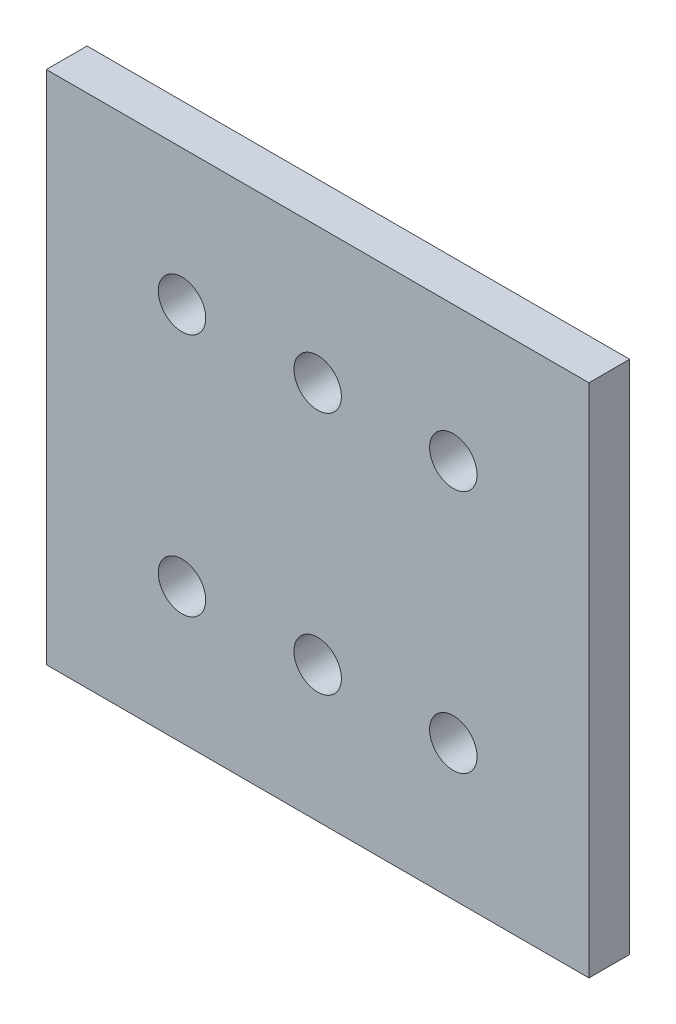
SolidWorks part; units mm, degrees
ref_plane "Front Plane" through (0, 0, 0) normal (0, 0, 1) x (1, 0, 0)
ref_plane "Top Plane" through (0, 0, 0) normal (0, 1, 0) x (1, 0, 0)
ref_plane "Right Plane" through (0, 0, 0) normal (1, 0, 0) x (0, 0, -1)
sketch "Sketch1" plane through (0, 0, 0) normal (0, 0, 1) x (1, 0, 0)
  line L1 (0, 0) -> (40, 0)
  line L2 (0, 0) -> (0, 38)
  line L3 (0, 38) -> (40, 38)
  line L4 (40, 0) -> (40, 38)
  circle A0 centre (10, 10) radius 1.75
  circle A1 centre (20, 10) radius 1.75
  circle A2 centre (30, 10) radius 1.75
  circle A3 centre (10, 28) radius 1.75
  circle A4 centre (20, 28) radius 1.75
  circle A5 centre (30, 28) radius 1.75
  dimension "D2" = 3.5
  dimension "D3" = 10
  dimension "D4" = 10
  dimension "D6" = 10
  dimension "D8" = 10
  dimension "D9" = 3.5
  dimension "D10" = 18
  dimension "D12" = 10
  dimension "D1" = 40
  dimension "D7" = 10
  dimension "D5" = 3
  dimension "D11" = 3
extrude "Boss-Extrude1" add sketch "Sketch1" along normal blind 3
